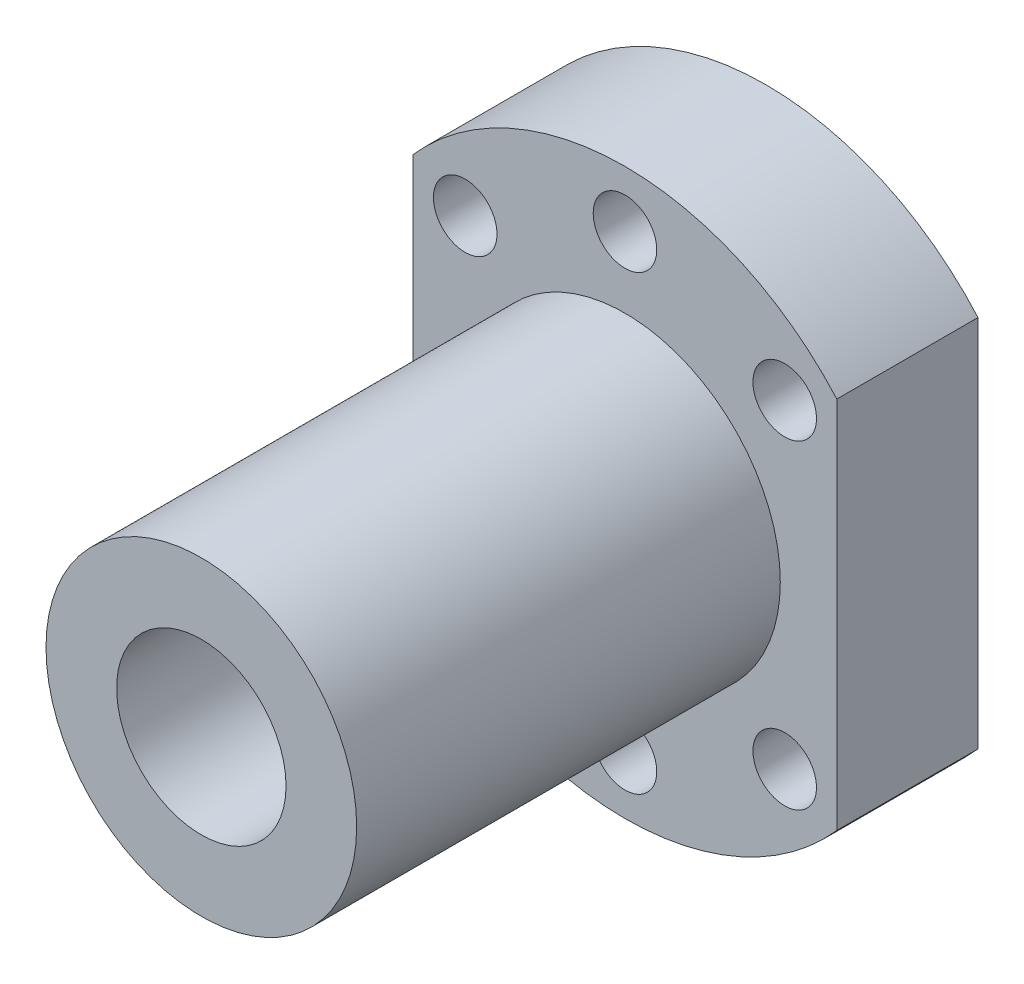
SolidWorks part; units mm, degrees
ref_plane "Front" through (0, 0, 0) normal (0, 0, 1) x (1, 0, 0)
ref_plane "Top" through (0, 0, 0) normal (0, 1, 0) x (1, 0, 0)
ref_plane "Right" through (0, 0, 0) normal (1, 0, 0) x (0, 0, -1)
sketch "Sketch1" plane through (0, 0, 0) normal (0, 0, 1) x (1, 0, 0)
  line L0 (-15, 13.2288) -> (-15, -13.2288)
  line L1 (15, 13.2288) -> (15, -13.2288)
  line L2 (0, -50) -> (0, 50) construction
  line L3 (0, 0) -> (0, 28.2531) construction
  arc A0 (-15, 13.2288) -> (15, 13.2288) centre (0, 0) cw
  arc A1 (-15, -13.2288) -> (15, -13.2288) centre (0, 0) ccw
  dimension "D2" = 20
  dimension "D1" = 30
extrude "Boss-Extrude1" add sketch "Sketch1" along normal blind 10
sketch "Sketch2" plane through (0, 0, 0) normal (0, 0, -1) x (-1, 0, 0)
  circle A0 centre (0, 0) radius 11
  dimension "D1" = 22
extrude "Boss-Extrude2" add sketch "Sketch2" against normal blind 40
sketch "Sketch3" plane through (0, 0, 40) normal (0, 0, 1) x (1, 0, 0)
  circle A0 centre (0, 0) radius 6
  dimension "D1" = 12
extrude "Cut-Extrude1" cut sketch "Sketch3" against normal through all
sketch "Sketch4" plane through (0, 0, 0) normal (0, 0, -1) x (-1, 0, 0)
  line L0 (-11.3137, 11.3137) -> (0, 0) construction
  line L1 (0, 0) -> (0, 16) construction
  line L2 (11.3137, 11.3137) -> (0, 0) construction
  circle A0 centre (0, 0) radius 16 construction
  circle A1 centre (-11.3137, 11.3137) radius 2.25
  circle A2 centre (0, 16) radius 2.25
  circle A3 centre (11.3137, 11.3137) radius 2.25
  dimension "D1" = 32
  dimension "D2" = 4.5
  dimension "D3" = 45
  dimension "D4" = 45
extrude "Cut-Extrude2" cut sketch "Sketch4" against normal through all
mirror "Mirror1" about plane through (0, 0, 0) normal (0, 1, 0) of "Cut-Extrude2"
equation "\"flange_d\"= 40"
equation "\"flange_b\"= 30"
equation "\"flange_h\"= 10"
equation "\"nut_h\"= 40"
equation "\"nut_d\"= 22"
equation "\"d\"= 12"
equation "\"screws_d\"= 4.5"
equation "\"screws_placement_d\"= 32"
equation "\"D1@Sketch1\"=\"flange_b\""
equation "\"D2@Sketch1\"=\"flange_d\" / 2"
equation "\"D1@Boss-Extrude1\"=\"flange_h\""
equation "\"D1@Sketch2\"=\"nut_d\""
equation "\"D1@Boss-Extrude2\"=\"nut_h\""
equation "\"D1@Sketch3\"=\"d\""
equation "\"D1@Sketch4\"=\"screws_placement_d\""
equation "\"D2@Sketch4\"=\"screws_d\""
equation "\"D4@Sketch4\"=\"D3@Sketch4\""
